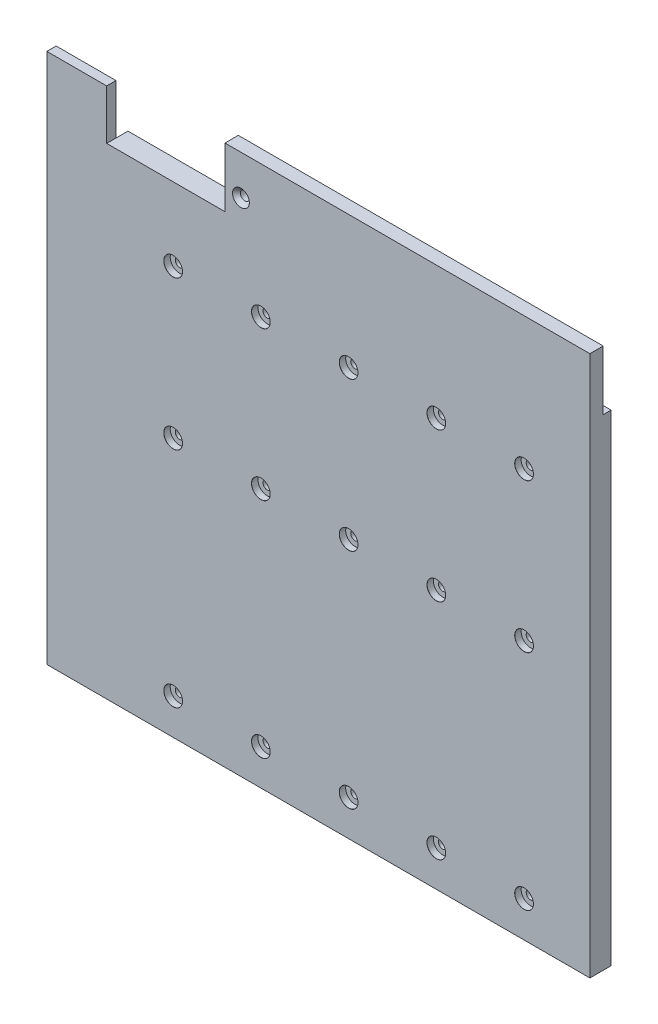
SolidWorks part; units mm, degrees
ref_plane "Plan de face" through (0, 0, 0) normal (0, 0, 1) x (1, 0, 0)
ref_plane "Plan de dessus" through (0, 0, 0) normal (0, 1, 0) x (1, 0, 0)
ref_plane "Plan de droite" through (0, 0, 0) normal (1, 0, 0) x (0, 0, -1)
sketch "Esquisse1" plane through (0, 0, 0) normal (0, 0, 1) x (1, 0, 0)
  line L1 (-204.25, -90.5) -> (204.25, -90.5)
  line L2 (-204.25, -90.5) -> (-204.25, 90.5)
  line L3 (-204.25, 90.5) -> (204.25, 90.5)
  line L4 (204.25, -90.5) -> (204.25, 90.5)
  line L5 (-204.25, -90.5) -> (204.25, 90.5) construction
  line L6 (-204.25, 90.5) -> (204.25, -90.5) construction
  point P0 (0, 0)
  dimension "D1" = 181
  dimension "D2" = 408.5
extrude "Boss.-Extru.1" add sketch "Esquisse1" along normal blind 8 contours L3 L4 L1 L2
hole_wizard "Chambrage pour vis à tête ronde bombée M31" positions "Esquisse2" profile "Esquisse3" counterbore size "M3" standard "Ansi Metric" end condition through all
sketch "Esquisse2" plane through (0, 0, 8) normal (0, 0, 1) x (1, 0, 0)
  point P0 (-156.75, 63)
  point P3 (-156.75, 7)
  point P6 (-156.75, -77)
sketch "Esquisse3" plane through (-156.75, 63, 8) normal (1, 0, 0) x (0, -1, 0)
  line L0 (0, 0) -> (0, 8)
  line L1 (0, 8) -> (1.6, 8)
  line L3 (1.6, 8) -> (1.6, 2.4)
  line L4 (3.5, 2.4) -> (1.6, 2.4)
  line L5 (3.5, 2.4) -> (3.5, 0.025)
  line L6 (3.5, 0.025) -> (3.525, 0)
  line L7 (3.525, 0) -> (0, 0)
  line L8 (-3.5, 0.025) -> (-3.525, 0) construction
  line L11 (0, -6.35) -> (0, 107.95) construction
  dimension "Diamètre du perçage jusqu'au prochain" = 3.2
  dimension "Profondeur du perçage jusqu'au prochain" = 8
  dimension "Diamètre du chambrage" = 7
  dimension "Profondeur du chambrage" = 2.4
  dimension "Diamètre du fraisage entrant" = 7.05
  dimension "Angle du fraisage entrant" = 90
pattern_linear "Répétition linéaire1" count 11 spacing 33 along (1, 0, 0) of "Chambrage pour vis à tête ronde bombée M31"
sketch "Esquisse4" plane through (0, 90.5, 0) normal (0, 1, 0) x (1, 0, 0)
  line L0 (-204.25, 0) -> (204.25, 0) construction
  line L1 (-204.25, 0) -> (-181.75, 0)
  line L2 (-204.25, 0) -> (-204.25, -4.5)
  line L3 (-204.25, -4.5) -> (-181.75, -4.5)
  line L4 (-181.75, 0) -> (-181.75, -4.5)
  line L5 (-204.25, -8) -> (204.25, -8) construction
  line L7 (0, -4.4) -> (0, 4.4) construction
  line L8 (181.75, 0) -> (181.75, -4.5)
  line L9 (204.25, -4.5) -> (181.75, -4.5)
  line L10 (204.25, 0) -> (204.25, -4.5)
  line L11 (204.25, 0) -> (181.75, 0)
  line L12 (-204.25, -8) -> (-204.25, 0) construction
  dimension "D1" = 3.5
  dimension "D3" = 22.5
extrude "Enlèv. mat.-Extru.1" cut sketch "Esquisse4" against normal up to surface (181 mm away) up to face at (0, -90.5, 4)
sketch "Esquisse5" plane through (0, 0, 8) normal (0, 0, 1) x (1, 0, 0)
  line L1 (-204.25, 90.5) -> (-181.75, 90.5)
  line L2 (-204.25, 90.5) -> (-204.25, 109.225)
  line L3 (-204.25, 109.225) -> (-181.75, 109.225)
  line L4 (-181.75, 90.5) -> (-181.75, 109.225)
  line L6 (-204.25, 90.5) -> (204.25, 90.5) construction
  dimension "D1" = 22.5
  dimension "D2" = 18.725
extrude "Boss.-Extru.2" add sketch "Esquisse5" against normal up to surface (3.5 mm away) up to face at (-193, 0, 4.5)
mirror "Symétrie1" about plane through (0, 0, 0) normal (1, 0, 0) of "Boss.-Extru.2"
sketch "Esquisse7" plane through (0, 0, 8) normal (0, 0, 1) x (1, 0, 0)
  line L0 (-181.75, 90.5) -> (181.75, 90.5) construction
  line L1 (-137.25, 90.5) -> (137.25, 90.5)
  line L2 (-137.25, 90.5) -> (-137.25, 112.875)
  line L3 (-137.25, 112.875) -> (137.25, 112.875)
  line L4 (137.25, 90.5) -> (137.25, 112.875)
  line L5 (137.75, 91) -> (137.75, 116.55) construction
  line L6 (-137.75, 91) -> (-137.75, 116.55) construction
  line L7 (-124.75, 113.375) -> (-137.75, 113.375) construction
  dimension "D1" = 0.5
  dimension "D2" = 0.5
  dimension "D3" = 0.5
extrude "Boss.-Extru.3" add sketch "Esquisse7" against normal blind 5
hole_wizard "Fraisage pour vis à tête fraisée M31" positions "Esquisse8" profile "Esquisse9" countersink size "M3" standard "Ansi Metric" end condition through all
sketch "Esquisse8" plane through (0, 0, 8) normal (0, 0, 1) x (1, 0, 0)
  point P0 (-131.25, 98)
  point P3 (131.25, 98)
sketch "Esquisse9" plane through (-131.25, 98, 8) normal (1, 0, 0) x (0, -1, 0)
  line L0 (0, 0) -> (0, 8)
  line L1 (0, 8) -> (1.7, 8)
  line L2 (1.7, 8) -> (1.7, 1.45)
  line L3 (1.7, 1.45) -> (3.15, 0)
  line L5 (3.15, 0) -> (0, 0)
  line L6 (-1.7, 1.45) -> (-3.15, 0) construction
  line L11 (0, -6.35) -> (0, 107.95) construction
  dimension "Diamètre du perçage jusqu'au prochain" = 3.4
  dimension "Profondeur du perçage jusqu'au prochain" = 8
  dimension "Diamètre du fraisage entrant" = 6.3
  dimension "Angle du fraisage entrant" = 90
sketch "Esquisse10" plane through (0, 0, 0) normal (0, 0, -1) x (-1, 0, 0)
  line L0 (181.75, -90.5) -> (-181.75, -90.5) construction
  line L1 (0, -90.5) -> (-205.3898, -90.5)
  line L2 (0, -90.5) -> (0, 116.2961)
  line L3 (0, 116.2961) -> (-205.3898, 116.2961)
  line L4 (-205.3898, -90.5) -> (-205.3898, 116.2961)
extrude "Enlèv. mat.-Extru.2" cut sketch "Esquisse10" against normal blind 10
